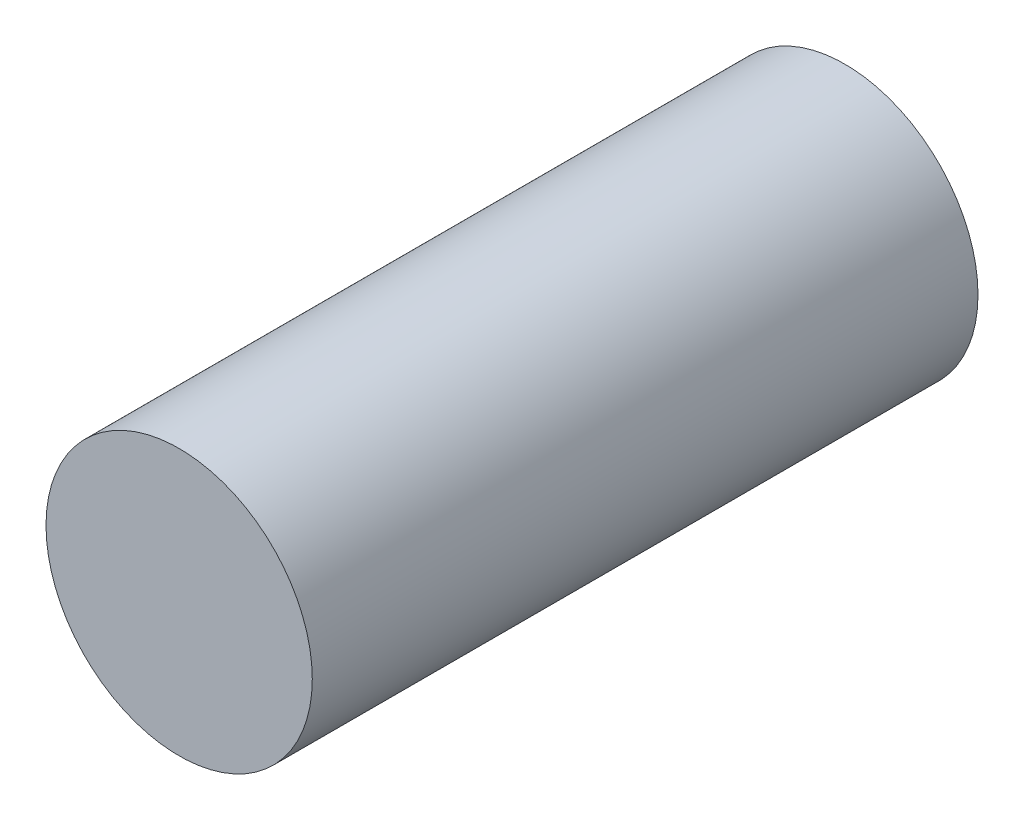
SolidWorks part; units mm, degrees
material "1060 Alloy"
ref_plane "Front Plane" through (0, 0, 0) normal (0, 0, 1) x (1, 0, 0)
ref_plane "Top Plane" through (0, 0, 0) normal (0, 1, 0) x (1, 0, 0)
ref_plane "Right Plane" through (0, 0, 0) normal (1, 0, 0) x (0, 0, -1)
sketch "Sketch1" plane through (0, 0, 0) normal (0, 0, 1) x (1, 0, 0)
  circle A0 centre (0, 0) radius 5.08
  dimension "D1" = 10.16
extrude "Boss-Extrude1" add sketch "Sketch1" along normal blind 25.4
